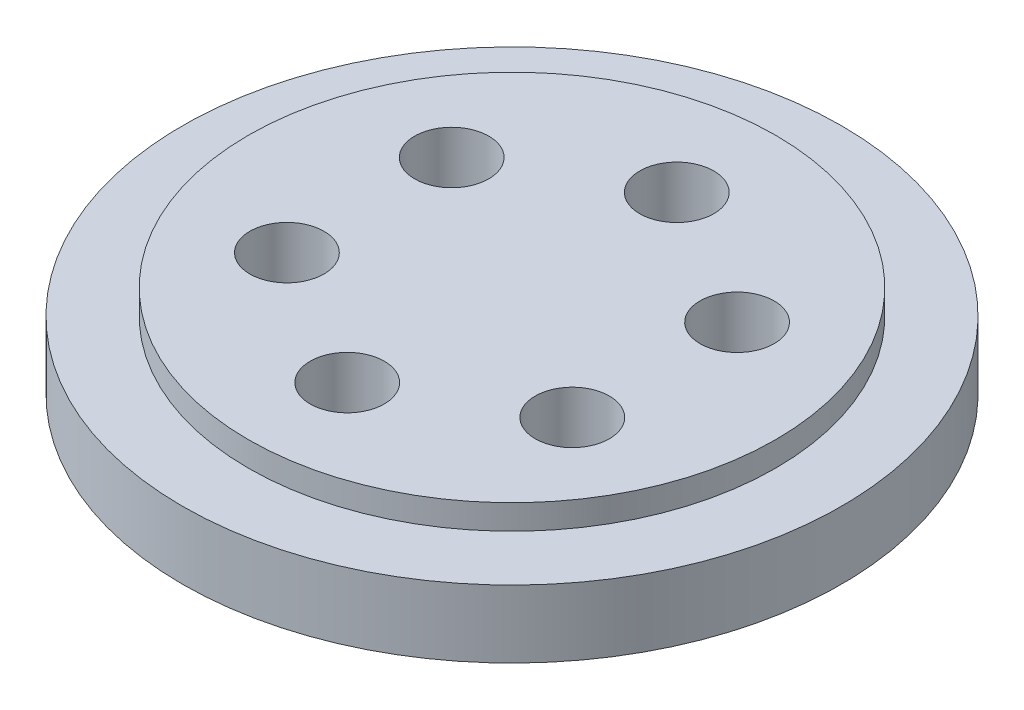
SolidWorks part; units mm, degrees
ref_plane "Ebene vorne" through (0, 0, 0) normal (0, 0, 1) x (1, 0, 0)
ref_plane "Ebene oben" through (0, 0, 0) normal (0, 1, 0) x (1, 0, 0)
ref_plane "Ebene rechts" through (0, 0, 0) normal (1, 0, 0) x (0, 0, -1)
sketch "Skizze1" plane through (0, 0, 0) normal (0, 1, 0) x (1, 0, 0)
  circle A0 centre (0, 0) radius 20
  dimension "D1" = 40
extrude "Aufsatz-Linear austragen1" add sketch "Skizze1" along normal blind 5.6
sketch "Skizze2" plane through (0, 5.6, 0) normal (0, 1, 0) x (1, 0, 0)
  circle A0 centre (0, 0) radius 16
  circle A1 centre (0, 0) radius 20 construction
  circle A2 centre (0, 0) radius 20
  dimension "D1" = 32
extrude "Schnitt-Linear austragen1" cut sketch "Skizze2" against normal blind 1.5
sketch "Skizze6" plane through (0, 5.6, 0) normal (0, 1, 0) x (1, 0, 0)
  circle A0 centre (0, 0) radius 10 construction
  dimension "D1" = 20
hole_wizard "Durchgangsloch für M41" positions "Skizze8" profile "Skizze9" hole size "M4" standard "ISO" end condition through all
sketch "Skizze8" plane through (0, 5.6, 0) normal (0, 1, 0) x (1, 0, 0)
  circle A0 centre (0, 0) radius 10 construction
  point P0 (0, 10)
  point P8 (8.6603, 5)
  point P9 (8.6603, -5)
  point P10 (0, -10)
  point P11 (-8.6603, -5)
  point P12 (-8.6603, 5)
  dimension "D1" = 6
sketch "Skizze9" plane through (0, 5.6, -10) normal (1, 0, 0) x (0, 0, 1)
  line L0 (0, 0) -> (0, 5.6)
  line L1 (0, 5.6) -> (2.25, 5.6)
  line L2 (2.25, 5.6) -> (2.25, 0)
  line L5 (2.25, 0) -> (0, 0)
  line L11 (0, -6.35) -> (0, 107.95) construction
  dimension "Bohrerdurchmesser" = 4.5
  dimension "Bohrungstiefe" = 5.6
